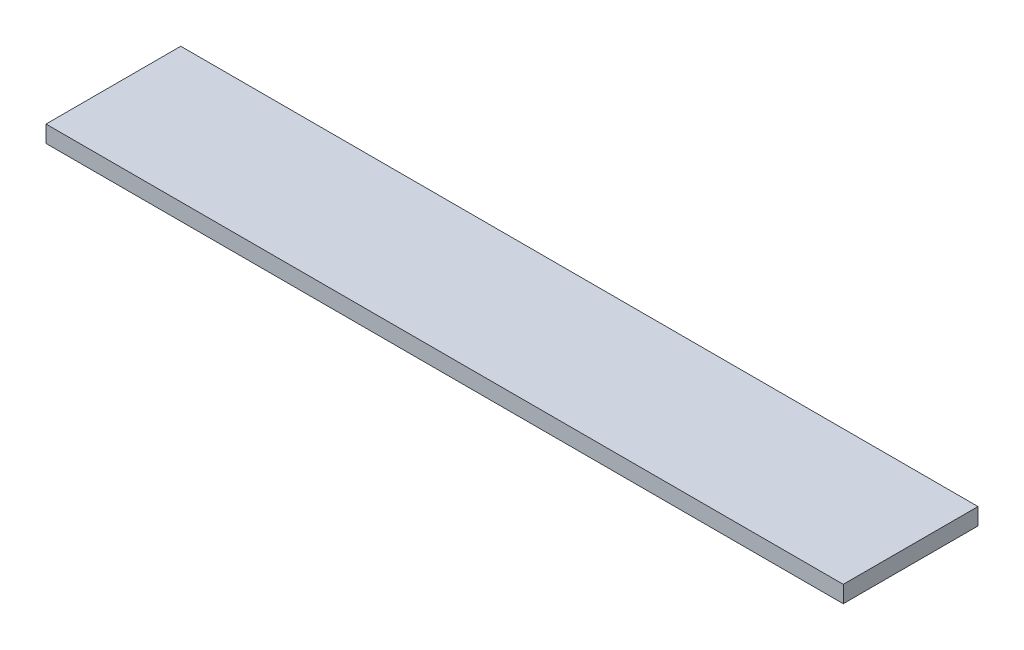
SolidWorks part; units mm, degrees
ref_plane "Front Plane" through (0, 0, 0) normal (0, 0, 1) x (1, 0, 0)
ref_plane "Top Plane" through (0, 0, 0) normal (0, 1, 0) x (1, 0, 0)
ref_plane "Right Plane" through (0, 0, 0) normal (1, 0, 0) x (0, 0, -1)
sketch "Sketch1" plane through (0, 0, 0) normal (0, 1, 0) x (1, 0, 0)
  line L1 (450.85, -76.2) -> (-450.85, -76.2)
  line L2 (450.85, -76.2) -> (450.85, 76.2)
  line L3 (450.85, 76.2) -> (-450.85, 76.2)
  line L4 (-450.85, -76.2) -> (-450.85, 76.2)
  line L5 (450.85, -76.2) -> (-450.85, 76.2) construction
  line L6 (450.85, 76.2) -> (-450.85, -76.2) construction
  point P0 (0, 0)
  dimension "D1" = 152.4
  dimension "D2" = 901.7
extrude "Boss-Extrude1" add sketch "Sketch1" along normal mid plane 19.05
